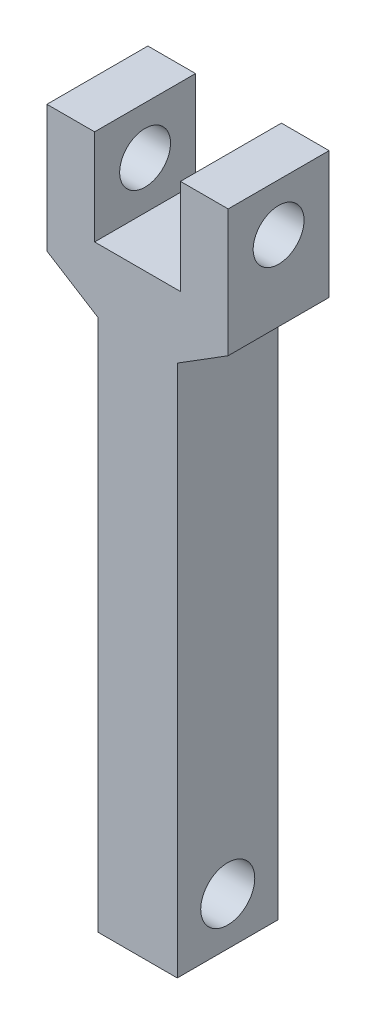
SolidWorks part; units mm, degrees
ref_plane "Front Plane" through (0, 0, 0) normal (0, 0, 1) x (1, 0, 0)
ref_plane "Top Plane" through (0, 0, 0) normal (0, 1, 0) x (1, 0, 0)
ref_plane "Right Plane" through (0, 0, 0) normal (1, 0, 0) x (0, 0, -1)
sketch "Sketch1" plane through (0, 0, 0) normal (0, 0, 1) x (1, 0, 0)
  line L0 (-306.0846, 0) -> (14998.1432, 0) construction
  line L1 (-306.5773, 37.5) -> (14997.6504, 37.5) construction
  line L2 (0, -1000) -> (0, 49000) construction
  line L3 (-2.5, -3) -> (2.5, -3)
  line L4 (2.5, -3) -> (2.5, 30.5)
  line L5 (2.5, 30.5) -> (5.7, 32.5)
  line L6 (5.7, 32.5) -> (5.7, 40.5)
  line L7 (5.7, 40.5) -> (2.7, 40.5)
  line L8 (2.7, 40.5) -> (2.7, 34.5)
  line L9 (2.7, 34.5) -> (-2.7, 34.5)
  line L10 (-2.7, 40.5) -> (-2.7, 34.5)
  line L11 (-5.7, 40.5) -> (-2.7, 40.5)
  line L12 (-5.7, 32.5) -> (-5.7, 40.5)
  line L13 (-2.5, 30.5) -> (-5.7, 32.5)
  line L14 (-2.5, -3) -> (-2.5, 30.5)
  point P16 (2.7, 37.5)
  point P19 (0, 34.5)
  point P24 (0, -3)
  dimension "link_length" = 37.5
  dimension "link_thickness" = 5
  dimension "D3" = 3
  dimension "D4" = 3
  dimension "clearance_from_insert" = 2
  dimension "angled_distance" = 2
  dimension "double_upright_thickness" = 3
  dimension "double_joint" = 5.4
extrude "Boss-Extrude1" add sketch "Sketch1" along normal mid plane 6.35
sketch "Sketch2" plane through (0, 0, 0) normal (1, 0, 0) x (0, 0, -1)
  line L0 (-1000, 37.5) -> (49000, 37.5) construction
  line L1 (-1000, 0) -> (49000, 0) construction
  line L2 (-3.175, 40.5) -> (3.175, 40.5) construction
  circle A0 centre (0, 0) radius 1.7
  circle A1 centre (0, 37.5) radius 1.6
  point P12 (0, 40.5)
  dimension "link_length" = 37.5
  dimension "D1" = 3.4
  dimension "D2" = 3.2
extrude "Cut-Extrude1" cut sketch "Sketch2" against normal through all both and the other way through all
sketch "Sketch3" [suppressed] plane through (2.5, 0, 0) normal (1, 0, 0) x (0, 0, -1)
  circle A0 centre (0, 37.5) radius 1.7
  circle A3 centre (0, 0) radius 1.7 construction
  dimension "D1" = 3.4
  dimension "D2" = 37.5
extrude "Cut-Extrude2" [suppressed] cut sketch "Sketch3" against normal through all both and the other way through all
equation "\"small_link\"= 15"
equation "\"linkage_distance\"= \"small_link\" * 2"
equation "\"link\"= \"small_link\" * 2.5"
equation "\"link_width\"= 0.25in"
equation "\"set_to_set_distance\"= 25mm"
equation "\"link_length@Sketch1\" = \"link\""
equation "\"link_thickness@Sketch1\"=\"link_thickness\""
equation "\"link_thickness\"= 5mm"
equation "\"double_joint@Sketch1\" = \"link_thickness\" + 0.4"
equation "\"D1@Boss-Extrude1\"=\"link_width\""
equation "\"link_length@Sketch2\" = \"link\""
equation "\"finger_pad_attach_thickness\"= 50mm"
equation "\"large_link\"= \"small_link\" * 5"
equation "\"D2@Sketch3\"=\"large_link\"/2"
